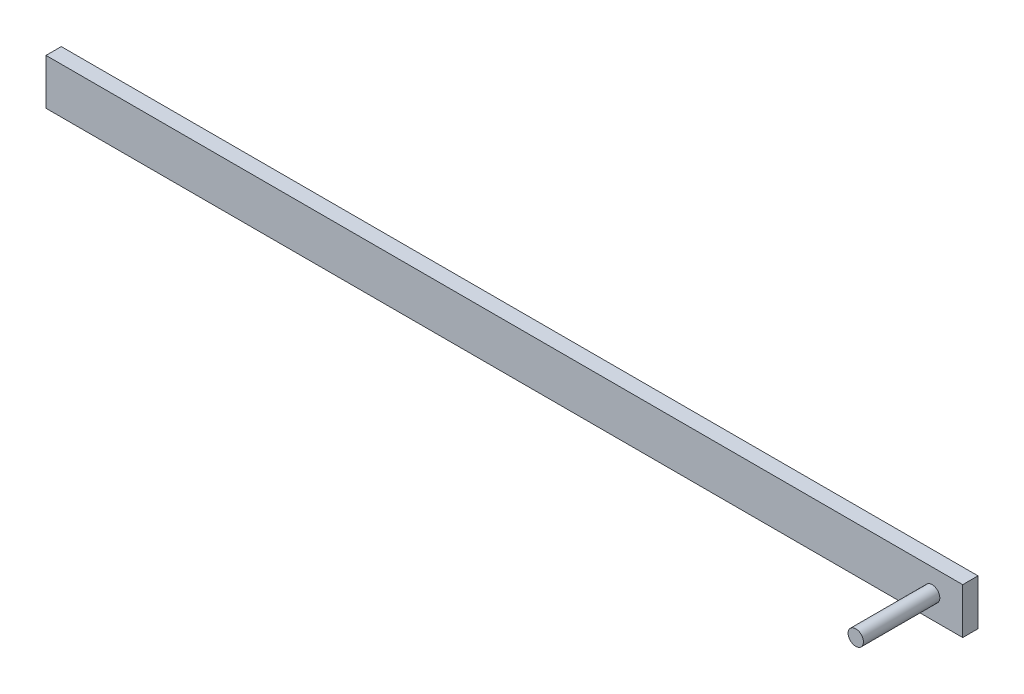
SolidWorks part; units mm, degrees
material "Oak"
ref_plane "Front Plane" through (0, 0, 0) normal (0, 0, 1) x (1, 0, 0)
ref_plane "Top Plane" through (0, 0, 0) normal (0, 1, 0) x (1, 0, 0)
ref_plane "Right Plane" through (0, 0, 0) normal (1, 0, 0) x (0, 0, -1)
sketch "Sketch1" plane through (0, 0, 0) normal (0, 0, 1) x (1, 0, 0)
  line L0 (-300, -15) -> (-300, 15)
  line L1 (-300, -15) -> (300, -15)
  line L2 (-300, 15) -> (300, 15)
  line L3 (300, -15) -> (300, 15)
  line L4 (0, 15) -> (0, -15) construction
  line L5 (-300, 0) -> (300, 0) construction
  point P1 (0, 0)
  dimension "D1" = 600
  dimension "D2" = 30
extrude "Boss-Extrude1" add sketch "Sketch1" along normal blind 10
sketch "Sketch2" plane through (0, 0, 10) normal (0, 0, 1) x (1, 0, 0)
  line L0 (0, 15) -> (0, -15) construction
  line L1 (300, 0) -> (-300, 0) construction
  line L4 (-300, -15) -> (300, -15)
  line L5 (300, -15) -> (300, 15)
  line L6 (300, 15) -> (-300, 15)
  line L7 (-300, 15) -> (-300, -15)
  line L8 (-300, -15) -> (300, -15)
  line L9 (300, -15) -> (300, 15)
  line L10 (300, 15) -> (-300, 15)
  line L11 (-300, 15) -> (-300, -15)
  circle A0 centre (280, 0) radius 5
  dimension "D2" = 10
  dimension "D3" = 20
  dimension "D1" = 0
extrude "Boss-Extrude2" add sketch "Sketch2" along normal blind 50 contours A0
